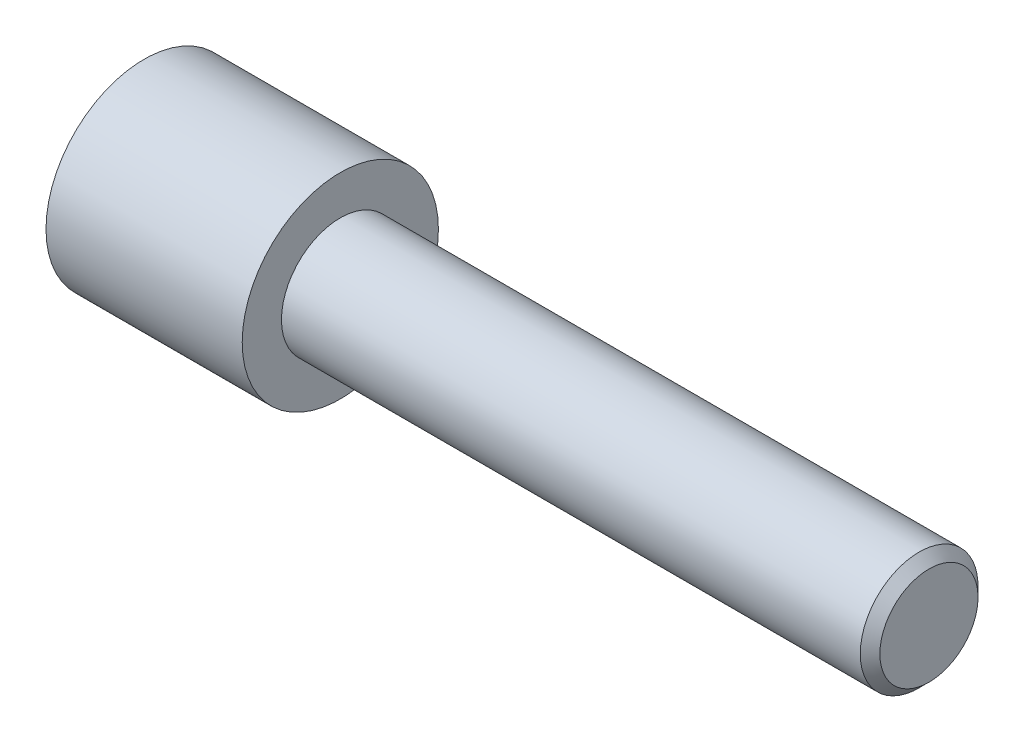
SolidWorks part; units mm, degrees
ref_plane "Front Plane" through (0, 0, 0) normal (0, 0, 1) x (1, 0, 0)
ref_plane "Top Plane" through (0, 0, 0) normal (0, 1, 0) x (1, 0, 0)
ref_plane "Right Plane" through (0, 0, 0) normal (1, 0, 0) x (0, 0, -1)
sketch "Sketch1" plane through (0, 0, 0) normal (0, 0, 1) x (1, 0, 0)
  line L0 (0, 0) -> (67.2727, 0) construction
  line L2 (0, 0) -> (60, 0)
  line L3 (0, 0) -> (0, 6)
  line L4 (0, 6) -> (60, 6)
  line L5 (60, 0) -> (60, 6)
  line L6 (0, 0) -> (-20, 0)
  line L7 (0, 0) -> (0, 10)
  line L8 (0, 10) -> (-20, 10)
  line L9 (-20, 0) -> (-20, 10)
  dimension "D1" = 60
  dimension "D2" = 6
  dimension "D3" = 20
  dimension "D4" = 10
revolve "Revolve1" add sketch "Sketch1" angle 360 about L0
chamfer "Chamfer1" distance 1 angle 45 1 edges at (60, 0, 6)
